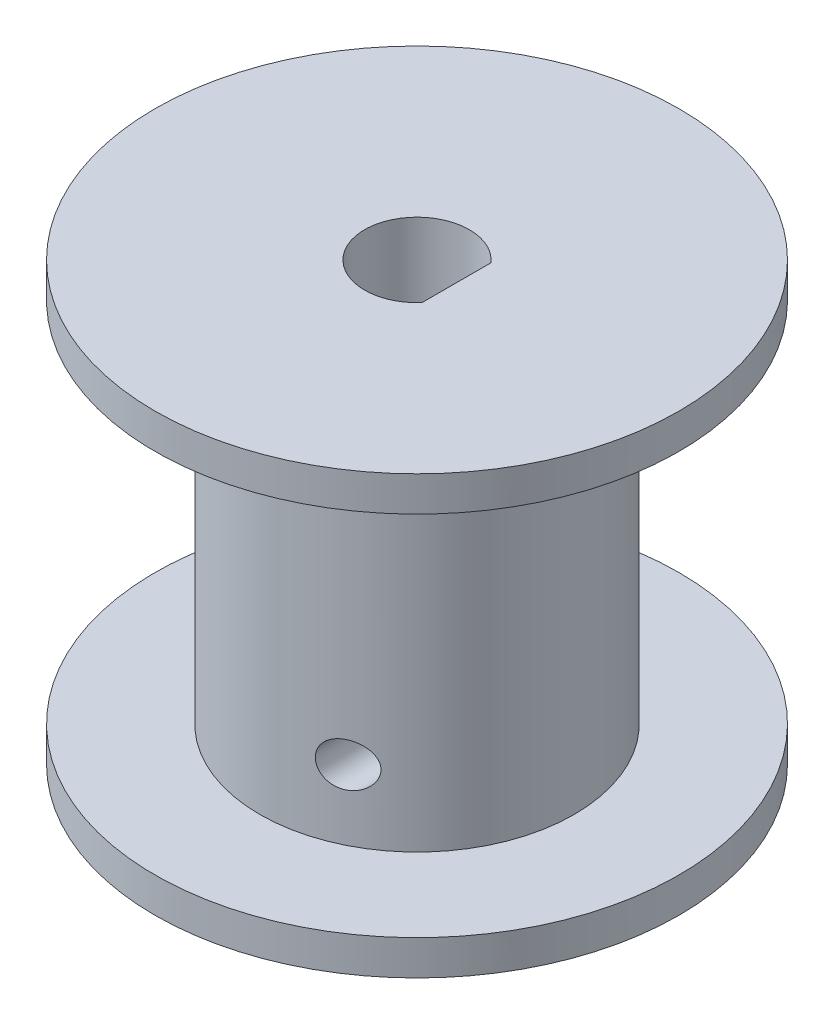
SolidWorks part; units mm, degrees
ref_plane "Front Plane" through (0, 0, 0) normal (0, 0, 1) x (1, 0, 0)
ref_plane "Top Plane" through (0, 0, 0) normal (0, 1, 0) x (1, 0, 0)
ref_plane "Right Plane" through (0, 0, 0) normal (1, 0, 0) x (0, 0, -1)
sketch "Sketch1" plane through (0, 0, 0) normal (0, 1, 0) x (1, 0, 0)
  circle A0 centre (0, 0) radius 15
  dimension "D2" = 30
extrude "Boss-Extrude1" add sketch "Sketch1" along normal blind 25
sketch "Sketch2" plane through (0, 25, 0) normal (0, 1, 0) x (1, 0, 0)
  circle A0 centre (0, 0) radius 3
  dimension "D1" = 6
extrude "Cut-Extrude1" cut sketch "Sketch2" against normal blind 25 contours A0
sketch "Sketch3" plane through (0, 0, 0) normal (0, 1, 0) x (1, 0, 0)
  line L0 (2.26, 1.9729) -> (2.26, -1.9729)
  line L1 (2.26, 1.9729) -> (3.06, 1.9729)
  line L2 (3.06, 1.9729) -> (3.06, -1.9729)
  line L3 (3.06, -1.9729) -> (2.26, -1.9729)
  circle A0 centre (0, 0) radius 3 construction
  dimension "D1" = 2.26
  dimension "D2" = 0.8
extrude "Boss-Extrude2" add sketch "Sketch3" along normal blind 25
sketch "Sketch4" plane through (0, 0, 0) normal (0, 0, 1) x (1, 0, 0)
  circle A0 centre (4, 6) radius 1.25
  dimension "D1" = 2.5
  dimension "D2" = 6
  dimension "D3" = 4
extrude "Cut-Extrude2" cut sketch "Sketch4" against normal blind 25 and the other way blind 2000
sketch "Sketch5" plane through (0, 0, 0) normal (0, 0, 1) x (1, 0, 0)
  line L0 (15, 0) -> (15, 25) construction
  line L1 (15, 2) -> (9, 2)
  line L2 (15, 2) -> (15, 23)
  line L3 (15, 23) -> (9, 23)
  line L4 (9, 2) -> (9, 23)
  line L5 (-15, 0) -> (15, 0) construction
  line L6 (15, 25) -> (-15, 25) construction
  line L7 (0, 0) -> (0, 25) construction
  point P13 (0, 24.0424)
  dimension "D1" = 2
  dimension "D2" = 2
  dimension "D3" = 6
revolve "Cut-Revolve1" cut sketch "Sketch5" angle 360 about L7
